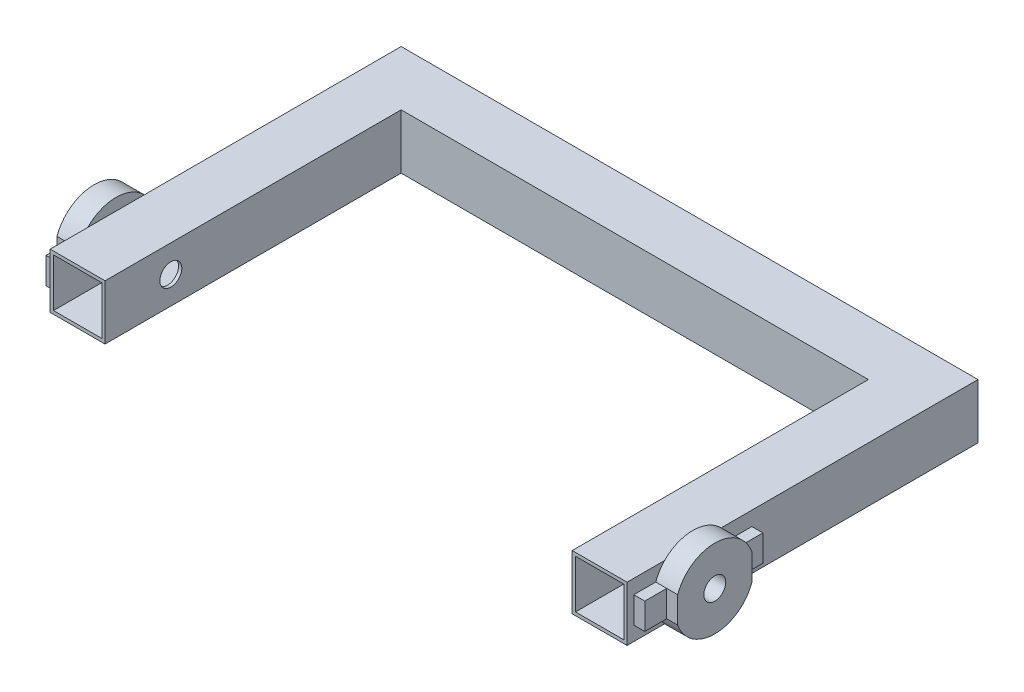
SolidWorks part; units mm, degrees
ref_plane "Front Plane" through (0, 0, 0) normal (0, 0, 1) x (1, 0, 0)
ref_plane "Top Plane" through (0, 0, 0) normal (0, 1, 0) x (1, 0, 0)
ref_plane "Right Plane" through (0, 0, 0) normal (1, 0, 0) x (0, 0, -1)
sketch "Sketch3" plane through (0, 0, 0) normal (0, 0, 1) x (1, 0, 0)
  line L0 (-46.4043, -11) -> (-24.4043, -11)
  line L1 (-47.9043, 12.5) -> (-22.9043, 12.5)
  line L2 (-47.9043, 12.5) -> (-47.9043, -12.5)
  line L3 (-47.9043, -12.5) -> (-22.9043, -12.5)
  line L4 (-22.9043, 12.5) -> (-22.9043, -12.5)
  line L5 (-47.9043, 12.5) -> (-22.9043, -12.5) construction
  line L6 (-47.9043, -12.5) -> (-22.9043, 12.5) construction
  line L7 (-24.4043, 11) -> (-24.4043, -11)
  line L8 (-46.4043, 11) -> (-24.4043, 11)
  line L9 (-46.4043, 11) -> (-46.4043, -11)
  point P0 (-35.4043, 0)
  dimension "D1" = 25
  dimension "D2" = 25
  dimension "D3" = 1.5
extrude "Boss-Extrude1" add sketch "Sketch3" along normal blind 160
sketch "Sketch4" plane through (-22.9043, 0, 0) normal (1, 0, 0) x (0, 0, -1)
  line L0 (-160, -12.5) -> (0, -12.5) construction
  line L1 (-25, 12.5) -> (0, 12.5)
  line L2 (-25, 12.5) -> (-25, -12.5)
  line L3 (-25, -12.5) -> (0, -12.5)
  line L4 (0, 12.5) -> (0, -12.5)
  line L5 (-25, 12.5) -> (0, -12.5) construction
  line L6 (-25, -12.5) -> (0, 12.5) construction
  line L7 (0, -12.5) -> (0, 12.5) construction
  line L8 (-23.5, -11) -> (-1.5, -11)
  line L9 (-1.5, 11) -> (-1.5, -11)
  line L10 (-23.5, 11) -> (-1.5, 11)
  line L11 (-23.5, 11) -> (-23.5, -11)
  point P0 (-12.5, 0)
  dimension "D1" = 25
  dimension "D2" = 25
  dimension "D3" = 0
  dimension "D4" = 1.5
extrude "Boss-Extrude2" add sketch "Sketch4" along normal blind 106.5
sketch "Sketch5" plane through (-47.9043, 0, 0) normal (-1, 0, 0) x (0, 0, 1)
  line L0 (160, 12.5) -> (160, -12.5) construction
  line L14 (146.9177, 6) -> (156.9177, 6)
  line L15 (146.9177, -6) -> (156.9177, -6)
  line L16 (156.9177, 6) -> (156.9177, -6)
  line L17 (113.0823, -6) -> (103.0823, -6)
  line L18 (103.0823, -6) -> (103.0823, 6)
  line L19 (103.0823, 6) -> (113.0823, 6)
  circle A1 centre (130, 0) radius 5
  circle A5 centre (130, 0) radius 17.9502
  arc A6 (146.9177, 6) -> (146.9177, -6) centre (130, 0) cw
  arc A7 (113.0823, 6) -> (113.0823, -6) centre (130, 0) ccw
  line M24 (0, -12.5) -> (160, -12.5)
  line M26 (160, 12.5) -> (0, 12.5)
  dimension "D1" = 30
  dimension "D2" = 10
  dimension "D5" = 6
  dimension "D3" = 10
  dimension "D4" = 12
  dimension "D6" = 10
  dimension "D7" = 10
  dimension "D8" = 12
extrude "Boss-Extrude3" add sketch "Sketch5" along normal blind 10 contours A5 L19 L18 L17 | A5 A1 M26 M24 | A5 L15 L16 L14 | A5 M26 | A5 M24
sketch "Sketch6" plane through (-57.9043, 0, 0) normal (-1, 0, 0) x (0, 0, 1)
  line L0 (103.0823, 6) -> (113.0823, 6)
  line L1 (113.0823, 6) -> (113.0823, -6)
  line L2 (113.0823, -6) -> (103.0823, -6)
  line L3 (103.0823, -6) -> (103.0823, 6)
  line L4 (146.9177, 6) -> (146.9177, -6)
  line L5 (146.9177, -6) -> (156.9177, -6)
  line L6 (156.9177, -6) -> (156.9177, 6)
  line L7 (156.9177, 6) -> (146.9177, 6)
extrude "Cut-Extrude1" cut sketch "Sketch6" against normal blind 5
sketch "Sketch7" plane through (-47.9043, 0, 0) normal (-1, 0, 0) x (0, 0, 1)
  circle A0 centre (130, 0) radius 5
extrude "Cut-Extrude2" cut sketch "Sketch7" against normal blind 25
mirror "Mirror1" about plane through (83.5957, 0, 0) normal (1, 0, 0) of "Boss-Extrude1", "Boss-Extrude2", "Boss-Extrude3", "Cut-Extrude1", "Cut-Extrude2"
